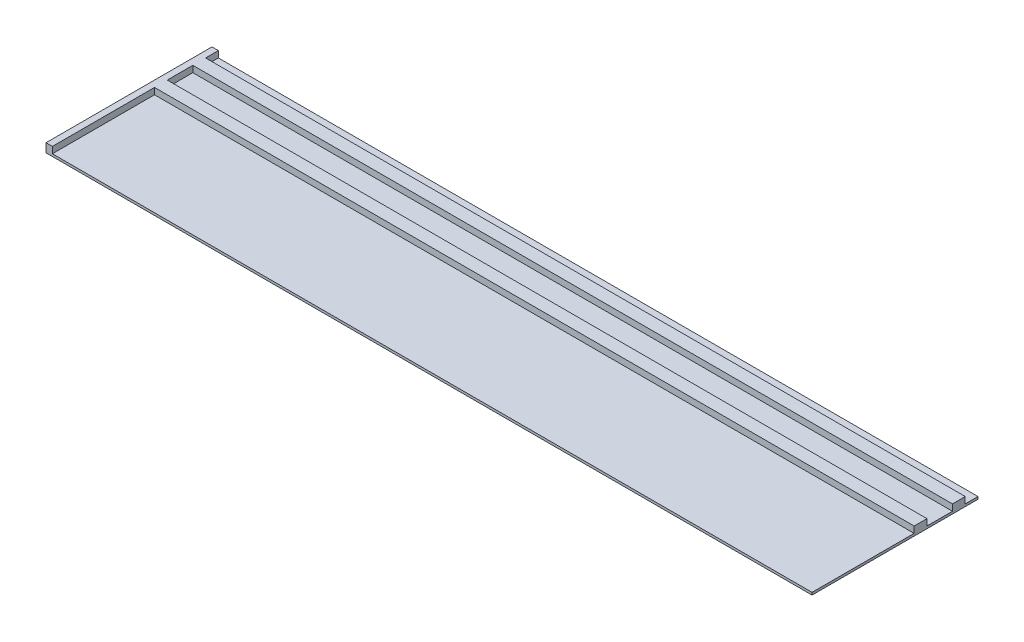
SolidWorks part; units mm, degrees
ref_plane "Front Plane" through (0, 0, 0) normal (0, 0, 1) x (1, 0, 0)
ref_plane "Top Plane" through (0, 0, 0) normal (0, 1, 0) x (1, 0, 0)
ref_plane "Right Plane" through (0, 0, 0) normal (1, 0, 0) x (0, 0, -1)
sketch "Sketch1" plane through (0, 0, 0) normal (0, 1, 0) x (1, 0, 0)
  line L1 (-381, -82.55) -> (381, -82.55)
  line L2 (-381, -82.55) -> (-381, 82.55)
  line L3 (-381, 82.55) -> (381, 82.55)
  line L4 (381, -82.55) -> (381, 82.55)
  line L5 (-381, -82.55) -> (381, 82.55) construction
  line L6 (-381, 82.55) -> (381, -82.55) construction
  point P0 (0, 0)
  dimension "D1" = 762
  dimension "D2" = 165.1
extrude "Boss-Extrude1" add sketch "Sketch1" along normal blind 2.3813
sketch "Sketch2" plane through (0, 2.3813, 0) normal (0, 1, 0) x (1, 0, 0)
  line L0 (381, -82.55) -> (381, 82.55) construction
  line L1 (-381, 19.05) -> (381, 19.05)
  line L2 (-381, 19.05) -> (-381, 69.85)
  line L3 (-381, 69.85) -> (381, 69.85)
  line L4 (381, 19.05) -> (381, 69.85)
  line L5 (-381, -82.55) -> (381, -82.55) construction
  dimension "D1" = 50.8
  dimension "D2" = 101.6
extrude "Boss-Extrude2" add sketch "Sketch2" along normal blind 6.35
sketch "Sketch3" plane through (0, 8.7312, 0) normal (0, 1, 0) x (1, 0, 0)
  line L1 (-381, 69.85) -> (-381, 19.05) construction
  line L2 (-381, 57.15) -> (381, 57.15)
  line L3 (-381, 57.15) -> (-381, 31.75)
  line L4 (-381, 31.75) -> (381, 31.75)
  line L5 (381, 57.15) -> (381, 31.75)
  line L6 (381, 19.05) -> (381, 69.85) construction
  line L7 (381, 69.85) -> (-381, 69.85) construction
  point P0 (0, 0)
  dimension "D1" = 25.4
  dimension "D2" = 12.7
extrude "Cut-Extrude1" cut sketch "Sketch3" against normal blind 6.35
sketch "Sketch4" plane through (0, 2.3813, 0) normal (0, 1, 0) x (1, 0, 0)
  line L0 (-381, -82.55) -> (381, -82.55) construction
  line L6 (-381, 82.55) -> (-374.65, 82.55)
  line L7 (-381, 82.55) -> (-381, -82.55)
  line L8 (-381, -82.55) -> (-374.65, -82.55)
  line L9 (-374.65, 82.55) -> (-374.65, -82.55)
  dimension "D1" = 6.35
extrude "Boss-Extrude3" add sketch "Sketch4" along normal blind 6.35
